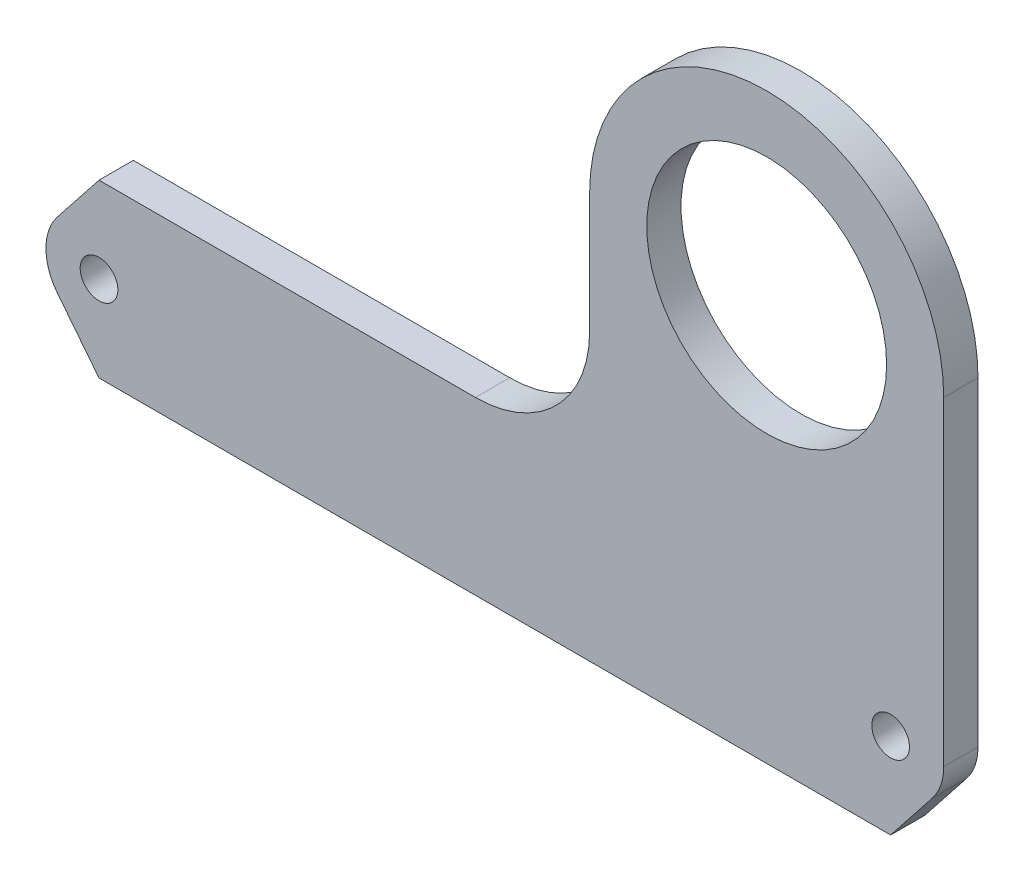
SolidWorks part; units mm, degrees
ref_plane "Front Plane" through (0, 0, 0) normal (0, 0, 1) x (1, 0, 0)
ref_plane "Top Plane" through (0, 0, 0) normal (0, 1, 0) x (1, 0, 0)
ref_plane "Right Plane" through (0, 0, 0) normal (1, 0, 0) x (0, 0, -1)
sketch "Sketch1" plane through (0, 0, 0) normal (0, 0, 1) x (1, 0, 0)
  line L0 (0, 7.5) -> (32.95, 7.5)
  line L1 (0, -7.5) -> (69.3, -7.5)
  line L2 (69.3, -7.5) -> (72.9484, -2.883)
  line L4 (0, 7.5) -> (-3.6484, 2.883)
  line L5 (0, -7.5) -> (-3.6484, -2.883)
  line L6 (58.45, 7.5) -> (58.45, 17.5) construction
  line L7 (73.95, 28) -> (73.95, 0)
  line L8 (42.95, 17.5) -> (42.95, 28)
  circle A0 centre (0, 0) radius 1.65
  circle A1 centre (69.3, 0) radius 1.65
  arc A2 (72.9484, -2.883) -> (73.95, 0) centre (69.3, 0) ccw
  arc A3 (-3.6484, 2.883) -> (-3.6484, -2.883) centre (0, 0) ccw
  circle A4 centre (0, 0) radius 4.65 construction
  circle A5 centre (69.3, 0) radius 4.65 construction
  circle A6 centre (58.45, 28) radius 10.5
  arc A7 (73.95, 28) -> (42.95, 28) centre (58.45, 28) ccw
  circle A8 centre (58.45, 28) radius 15.5 construction
  arc A9 (42.95, 17.5) -> (32.95, 7.5) centre (32.95, 17.5) cw
  dimension "D3" = 3.3
  dimension "D5" = 21
  dimension "D8" = 10
  dimension "D2" = 69.3
  dimension "D4" = 15
  dimension "D7" = 10
  dimension "D1" = 3
  dimension "D6" = 5
extrude "Boss-Extrude1" add sketch "Sketch1" along normal blind 3
